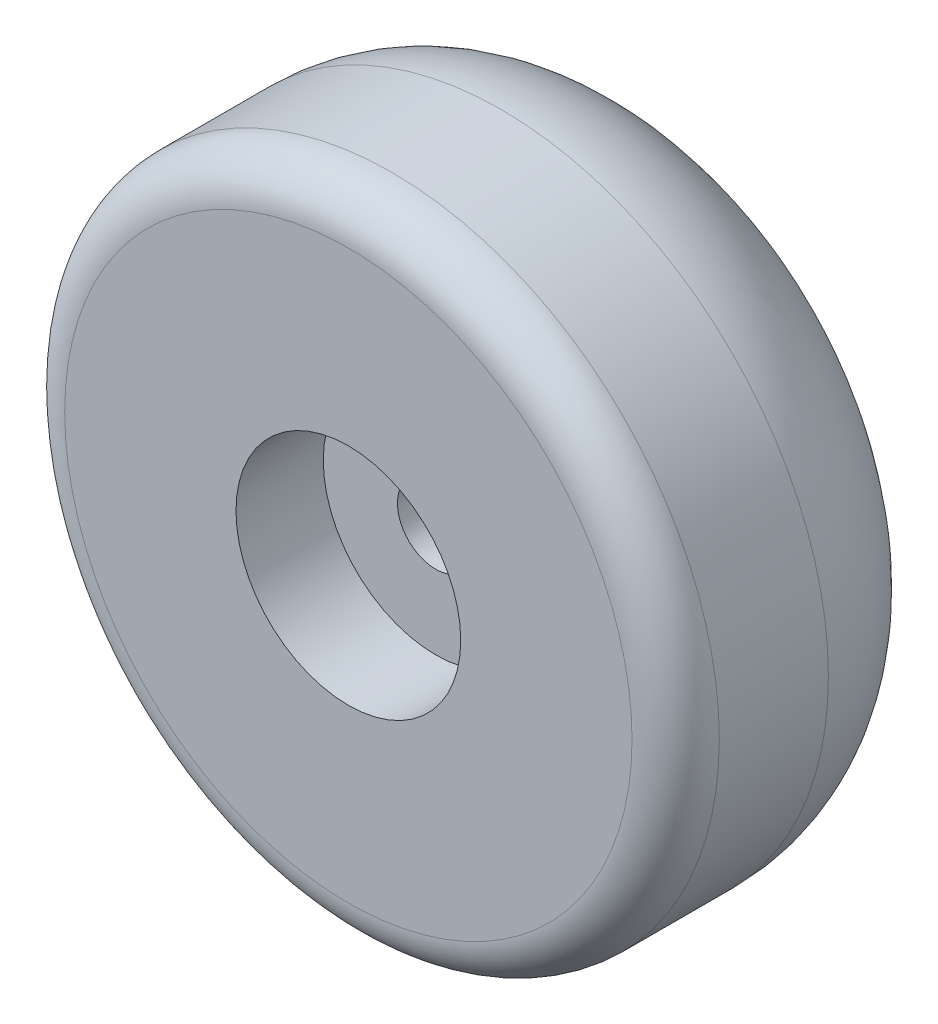
SolidWorks part; units mm, degrees
ref_plane "Спереди" through (0, 0, 0) normal (0, 0, 1) x (1, 0, 0)
ref_plane "Сверху" through (0, 0, 0) normal (0, 1, 0) x (1, 0, 0)
ref_plane "Справа" through (0, 0, 0) normal (1, 0, 0) x (0, 0, -1)
sketch "Эскиз1" plane through (0, 0, 0) normal (0, 0, 1) x (1, 0, 0)
  circle A0 centre (0, 0) radius 1.75
  circle A1 centre (0, 0) radius 15
  dimension "D1" = 3.5
  dimension "D2" = 30
extrude "Бобышка-Вытянуть1" add sketch "Эскиз1" along normal blind 14
sketch "Эскиз2" plane through (0, 0, 14) normal (0, 0, 1) x (1, 0, 0)
  circle A0 centre (0, 0) radius 5.15
  dimension "D1" = 10.3
extrude "Вырез-Вытянуть1" cut sketch "Эскиз2" against normal blind 4
fillet "Скругление1" radius 2 1 edges at (15, 0, 14)
fillet "Скругление2" radius 7 1 edges at (15, 0, 0)
